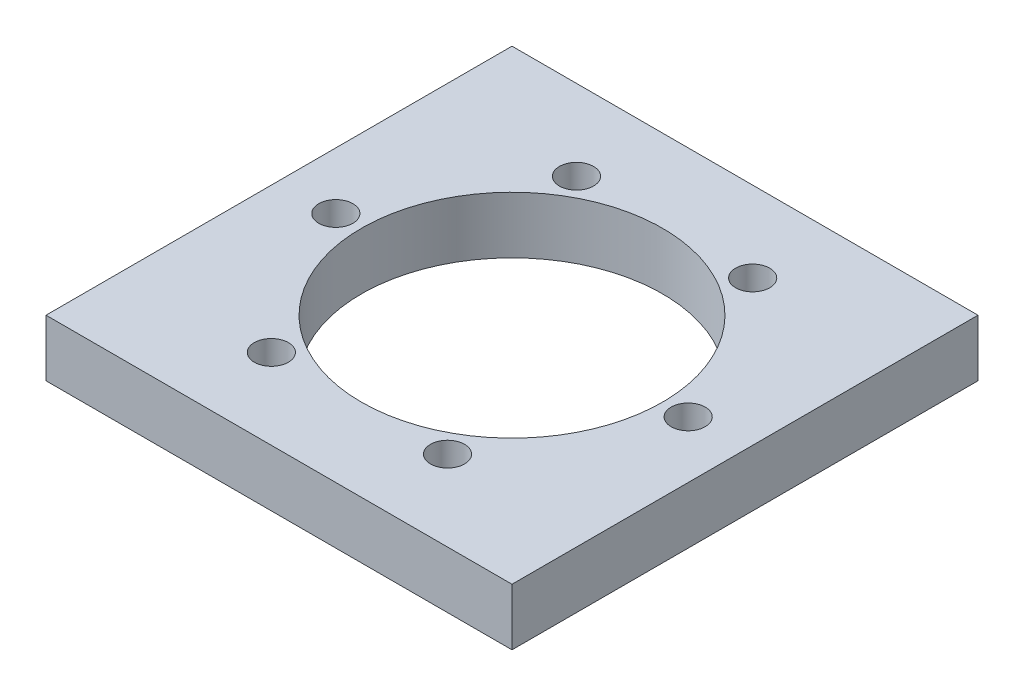
SolidWorks part; units mm, degrees
ref_plane "Front Plane" through (0, 0, 0) normal (0, 0, 1) x (1, 0, 0)
ref_plane "Top Plane" through (0, 0, 0) normal (0, 1, 0) x (1, 0, 0)
ref_plane "Right Plane" through (0, 0, 0) normal (1, 0, 0) x (0, 0, -1)
sketch "Sketch1" plane through (0, 0, 0) normal (0, 1, 0) x (1, 0, 0)
  circle A0 centre (0, 0) radius 18.5
  circle A1 centre (15.5, 0) radius 1.5
  circle A2 centre (7.75, -13.4234) radius 1.5
  circle A3 centre (-7.75, -13.4234) radius 1.5
  circle A4 centre (-15.5, 0) radius 1.5
  circle A5 centre (-7.75, 13.4234) radius 1.5
  circle A6 centre (7.75, 13.4234) radius 1.5
  circle A7 centre (0, 0) radius 13.25
  dimension "D1" = 3
  dimension "D2" = 37
  dimension "D3" = 26.5
  dimension "D4" = 3
  dimension "D5" = 3
  dimension "D6" = 3
  dimension "D7" = 3
  dimension "D8" = 3
sketch "Sketch2" plane through (0, 0, 0) normal (0, 1, 0) x (1, 0, 0)
  line L1 (-20.5, 20.5) -> (20.5, 20.5)
  line L2 (-20.5, 20.5) -> (-20.5, -20.5)
  line L3 (-20.5, -20.5) -> (20.5, -20.5)
  line L4 (20.5, 20.5) -> (20.5, -20.5)
  line L5 (-20.5, 20.5) -> (20.5, -20.5) construction
  line L6 (-20.5, -20.5) -> (20.5, 20.5) construction
  circle A0 centre (0, 0) radius 18.5 construction
  circle A1 centre (0, 0) radius 13.25 construction
  circle A2 centre (7.75, 13.4234) radius 1.5 construction
  circle A3 centre (-7.75, 13.4234) radius 1.5 construction
  circle A4 centre (-15.5, 0) radius 1.5 construction
  circle A5 centre (-7.75, -13.4234) radius 1.5 construction
  circle A6 centre (7.75, -13.4234) radius 1.5 construction
  circle A7 centre (15.5, 0) radius 1.5 construction
  circle A8 centre (15.5, 0) radius 1.5
  circle A9 centre (7.75, -13.4234) radius 1.5
  circle A10 centre (-7.75, -13.4234) radius 1.5
  circle A11 centre (-15.5, 0) radius 1.5
  circle A12 centre (-7.75, 13.4234) radius 1.5
  circle A13 centre (7.75, 13.4234) radius 1.5
  circle A14 centre (0, 0) radius 13.25
  circle A15 centre (0, 0) radius 18.5 construction
  point P0 (0, 0)
  dimension "D1" = 41
  dimension "D2" = 41
extrude "Boss-Extrude1" add sketch "Sketch2" along normal blind 5
